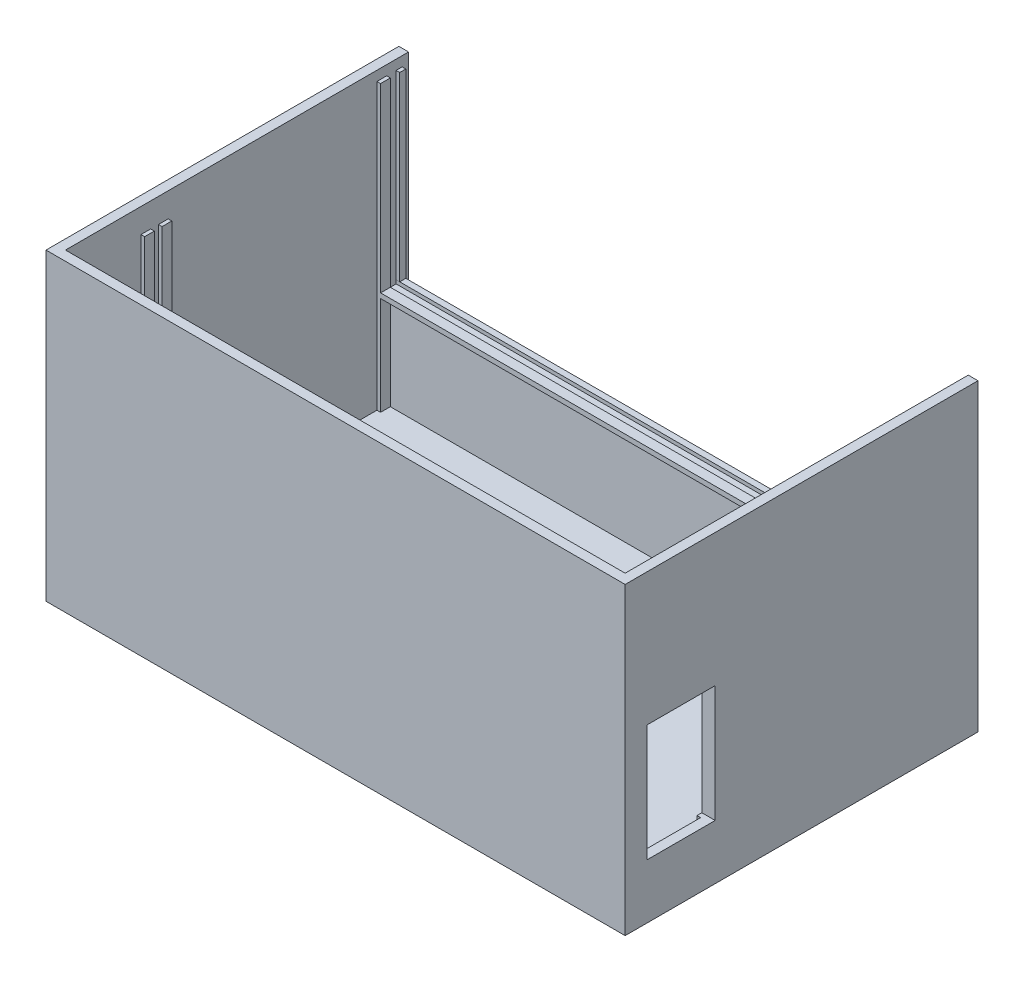
SolidWorks part; units mm, degrees
ref_plane "前视基准面" through (0, 0, 0) normal (0, 0, 1) x (1, 0, 0)
ref_plane "上视基准面" through (0, 0, 0) normal (0, 1, 0) x (1, 0, 0)
ref_plane "右视基准面" through (0, 0, 0) normal (1, 0, 0) x (0, 0, -1)
sketch "草图1" plane through (0, 0, 0) normal (0, 1, 0) x (1, 0, 0)
  line L1 (-86.1247, 66.7751) -> (151.8753, 66.7751)
  line L2 (-86.1247, 66.7751) -> (-86.1247, -73.2249)
  line L3 (-86.1247, -73.2249) -> (151.8753, -73.2249)
  line L4 (151.8753, 66.7751) -> (151.8753, -73.2249)
  dimension "D1" = 140
  dimension "D2" = 238
extrude "凸台-拉伸3" add sketch "草图1" along normal blind 125
shell "抽壳1" thickness 4
sketch "草图2" plane through (0, 0, -62.7751) normal (0, 0, 1) x (1, 0, 0)
  line L1 (-82.1247, 125) -> (-82.1247, 4) construction
  line L2 (147.8753, 125) -> (-82.1247, 125)
  line L3 (147.8753, 125) -> (147.8753, 45)
  line L4 (147.8753, 45) -> (-82.1247, 45)
  line L5 (-82.1247, 125) -> (-82.1247, 45)
  dimension "D1" = 80
extrude "切除-拉伸1" cut sketch "草图2" against normal blind 120
sketch "草图5" plane through (147.8753, 0, 0) normal (-1, 0, 0) x (0, 0, 1)
  line L0 (69.2249, 125) -> (-66.7751, 125) construction
  line L1 (-62.7751, 4) -> (-58.7751, 4)
  line L2 (-62.7751, 4) -> (-62.7751, 121)
  line L3 (-62.7751, 121) -> (-58.7751, 121)
  line L4 (-58.7751, 4) -> (-58.7751, 121)
  dimension "D1" = 4
  dimension "D2" = 4
extrude "凸台-拉伸6" add sketch "草图5" along normal blind 1.5
sketch "草图6" plane through (-82.1247, 0, 0) normal (1, 0, 0) x (0, 0, -1)
  line L0 (66.7751, 125) -> (-69.2249, 125) construction
  line L1 (62.7751, 4) -> (58.7751, 4)
  line L2 (62.7751, 4) -> (62.7751, 121)
  line L3 (62.7751, 121) -> (58.7751, 121)
  line L4 (58.7751, 4) -> (58.7751, 121)
  dimension "D1" = 4
  dimension "D2" = 4
extrude "凸台-拉伸7" add sketch "草图6" along normal blind 1.5
sketch "草图7" plane through (0, 0, -66.7751) normal (0, 0, -1) x (-1, 0, 0)
  line L0 (-151.8753, 125) -> (-147.8753, 125)
  line L1 (-147.8753, 125) -> (-147.8753, 4)
  line L2 (-147.8753, 4) -> (82.1247, 4)
  line L3 (82.1247, 4) -> (82.1247, 125)
  line L4 (82.1247, 125) -> (86.1247, 125)
  line L5 (86.1247, 125) -> (86.1247, 0)
  line L6 (86.1247, 0) -> (-151.8753, 0)
  line L7 (-151.8753, 0) -> (-151.8753, 125)
  line L8 (82.1247, 125) -> (82.1247, 45) construction
  dimension "D1" = 4
extrude "凸台-拉伸8" add sketch "草图7" along normal blind 5
sketch "草图8" plane through (147.8753, 0, 0) normal (-1, 0, 0) x (0, 0, 1)
  line L5 (-66.6457, 46.5) -> (-66.7751, 37.3879)
  line L6 (-66.7751, 4) -> (-66.7751, 45) construction
  line L7 (-66.7751, 37.3879) -> (-69.1457, 45)
  line L8 (-69.1457, 45) -> (-69.1457, 46.5)
  line L9 (-69.1457, 46.5) -> (-66.6457, 46.5)
  line L10 (-66.7751, 45) -> (-62.7751, 45) construction
  dimension "D1" = 1.5
  dimension "D2" = 2.5
  dimension "D3" = 1.5
extrude "凸台-拉伸9" add sketch "草图8" along normal blind 230
sketch "草图9" plane through (146.3753, 0, 0) normal (-1, 0, 0) x (0, 0, 1)
  line L0 (-62.7751, 46.5) -> (-58.7751, 46.5)
  line L1 (-62.7751, 121) -> (-62.7751, 45) construction
  line L2 (-58.7751, 4) -> (-58.7751, 121) construction
  line L3 (-58.7751, 46.5) -> (-58.7751, 44.5)
  line L4 (-58.7751, 44.5) -> (-62.7751, 43)
  line L5 (-62.7751, 45) -> (-62.7751, 4) construction
  line L6 (-62.7751, 43) -> (-62.7751, 46.5)
  line L7 (-66.667, 45) -> (-62.7751, 45) construction
  dimension "D1" = 1.5
  dimension "D2" = 2
  dimension "D3" = 2
extrude "凸台-拉伸10" add sketch "草图9" along normal blind 227
sketch "草图10" plane through (147.8753, 0, 0) normal (-1, 0, 0) x (0, 0, 1)
  line L0 (69.2249, 125) -> (-71.7751, 125) construction
  line L1 (-69.1457, 46.5) -> (-66.6457, 46.5)
  line L2 (-69.1457, 46.5) -> (-69.1457, 121)
  line L3 (-69.1457, 121) -> (-66.6457, 121)
  line L4 (-66.6457, 46.5) -> (-66.6457, 121)
  dimension "D1" = 4
extrude "凸台-拉伸11" add sketch "草图10" along normal blind 1.5
sketch "草图11" plane through (-82.1247, 0, 0) normal (1, 0, 0) x (0, 0, -1)
  line L0 (71.7751, 125) -> (-69.2249, 125) construction
  line L1 (69.1457, 46.5) -> (66.6457, 46.5)
  line L2 (69.1457, 46.5) -> (69.1457, 121)
  line L3 (69.1457, 121) -> (66.6457, 121)
  line L4 (66.6457, 46.5) -> (66.6457, 121)
  dimension "D1" = 4
extrude "凸台-拉伸12" add sketch "草图11" along normal blind 1.5
sketch "草图12" plane through (147.8753, 0, 0) normal (-1, 0, 0) x (0, 0, 1)
  line L0 (69.2249, 4) -> (-58.7751, 4) construction
  line L1 (38.2249, 4) -> (34.2249, 4)
  line L2 (38.2249, 4) -> (38.2249, 115)
  line L3 (38.2249, 115) -> (34.2249, 115)
  line L4 (34.2249, 4) -> (34.2249, 115)
  line L5 (-58.7751, 4) -> (-58.7751, 121) construction
  line L6 (69.2249, 125) -> (-71.7751, 125) construction
  line L8 (27.0249, 4) -> (31.0249, 4)
  line L9 (27.0249, 4) -> (27.0249, 115)
  line L10 (27.0249, 115) -> (31.0249, 115)
  line L11 (31.0249, 4) -> (31.0249, 115)
  dimension "D1" = 93
  dimension "D2" = 4
  dimension "D3" = 10
  dimension "D4" = 10
  dimension "D5" = 3.2
  dimension "D6" = 4
extrude "凸台-拉伸14" add sketch "草图12" along normal blind 1.5
sketch "草图13" plane through (147.8753, 0, 0) normal (-1, 0, 0) x (0, 0, 1)
  line L0 (69.2249, 4) -> (38.2249, 4) construction
  line L1 (69.2249, 4) -> (67.2249, 4)
  line L2 (69.2249, 4) -> (69.2249, 115)
  line L3 (69.2249, 115) -> (67.2249, 115)
  line L4 (67.2249, 4) -> (67.2249, 115)
  line L6 (69.2249, 125) -> (-71.7751, 125) construction
  line L7 (64.2249, 4) -> (60.2249, 4)
  line L8 (64.2249, 4) -> (64.2249, 115)
  line L9 (64.2249, 115) -> (60.2249, 115)
  line L10 (60.2249, 4) -> (60.2249, 115)
  line L11 (69.2249, 125) -> (69.2249, 4) construction
  dimension "D1" = 2
  dimension "D3" = 4
  dimension "D4" = 3
  dimension "D5" = 10
  dimension "D6" = 10
extrude "凸台-拉伸17" add sketch "草图13" along normal blind 1.5
sketch "草图14" plane through (146.3753, 0, 0) normal (-1, 0, 0) x (0, 0, 1)
  line L0 (64.2249, 4) -> (64.2249, 115) construction
  line L1 (36.2249, 79) -> (64.2249, 79) construction
  line L2 (36.2249, 79) -> (36.2249, 14) construction
  line L3 (36.2249, 14) -> (64.2249, 14) construction
  line L4 (64.2249, 79) -> (64.2249, 14) construction
  line L5 (60.2249, 4) -> (38.2249, 4) construction
  line L7 (36.2249, 22.5) -> (64.2249, 22.5)
  line L8 (36.2249, 22.5) -> (36.2249, 70.5)
  line L9 (36.2249, 70.5) -> (64.2249, 70.5)
  line L10 (64.2249, 22.5) -> (64.2249, 70.5)
  point P12 (36.2249, 46.5)
  point P13 (36.2249, 46.5)
  dimension "D1" = 65
  dimension "D2" = 28
  dimension "D3" = 10
  dimension "D4" = 48
extrude "切除-拉伸3" cut sketch "草图14" against normal blind 18
sketch "草图15" plane through (0, 0, -66.7751) normal (0, 0, -1) x (-1, 0, 0)
  line L1 (-147.8753, 4) -> (-147.8753, 37.3879) construction
  line L2 (-132.8753, 31.694) -> (-102.8753, 31.694)
  line L3 (-132.8753, 31.694) -> (-132.8753, 9.694)
  line L4 (-132.8753, 9.694) -> (-102.8753, 9.694)
  line L5 (-102.8753, 31.694) -> (-102.8753, 9.694)
  line L6 (-87.8753, 31.694) -> (-57.8753, 31.694)
  line L7 (-87.8753, 31.694) -> (-87.8753, 9.694)
  line L8 (-87.8753, 9.694) -> (-57.8753, 9.694)
  line L9 (-57.8753, 31.694) -> (-57.8753, 9.694)
  point P8 (-147.8753, 20.694)
  point P9 (-132.8753, 20.694)
  point P12 (-87.8753, 20.694)
  dimension "D1" = 22
  dimension "D2" = 22
  dimension "D3" = 30
  dimension "D4" = 30
  dimension "D5" = 15
  dimension "D6" = 15
extrude "切除-拉伸4" cut sketch "草图15" against normal blind 18
sketch "草图16" plane through (-82.1247, 0, 0) normal (1, 0, 0) x (0, 0, -1)
  line L0 (71.7751, 125) -> (-69.2249, 125) construction
  line L1 (-69.2249, 4) -> (-67.2249, 4)
  line L2 (-69.2249, 4) -> (-69.2249, 115)
  line L3 (-69.2249, 115) -> (-67.2249, 115)
  line L4 (-67.2249, 4) -> (-67.2249, 115)
  dimension "D1" = 2
  dimension "D2" = 10
extrude "凸台-拉伸18" add sketch "草图16" along normal blind 1.5
sketch "草图17" plane through (-82.1247, 0, 0) normal (1, 0, 0) x (0, 0, -1)
  line L0 (58.7751, 4) -> (-67.2249, 4) construction
  line L1 (-64.2249, 4) -> (-60.2249, 4)
  line L2 (-64.2249, 4) -> (-64.2249, 115)
  line L3 (-64.2249, 115) -> (-60.2249, 115)
  line L4 (-60.2249, 4) -> (-60.2249, 115)
  line L5 (71.7751, 125) -> (-69.2249, 125) construction
  line L6 (-69.2249, 125) -> (-69.2249, 115) construction
  dimension "D1" = 4
  dimension "D2" = 10
  dimension "D3" = 5
extrude "凸台-拉伸19" add sketch "草图17" along normal blind 1.5
sketch "草图19" plane through (-82.1247, 0, 0) normal (1, 0, 0) x (0, 0, -1)
  line L0 (58.7751, 4) -> (-60.2249, 4) construction
  line L1 (-38.2249, 4) -> (-34.2249, 4)
  line L2 (-38.2249, 4) -> (-38.2249, 115)
  line L3 (-38.2249, 115) -> (-34.2249, 115)
  line L4 (-34.2249, 4) -> (-34.2249, 115)
  line L5 (-69.2249, 125) -> (-69.2249, 115) construction
  line L6 (71.7751, 125) -> (-69.2249, 125) construction
  dimension "D1" = 4
  dimension "D2" = 31
  dimension "D3" = 10
extrude "凸台-拉伸20" add sketch "草图19" along normal blind 1.5
sketch "草图20" plane through (-82.1247, 0, 0) normal (1, 0, 0) x (0, 0, -1)
  line L0 (58.7751, 4) -> (-34.2249, 4) construction
  line L1 (-31.0249, 4) -> (-27.0249, 4)
  line L2 (-31.0249, 4) -> (-31.0249, 115)
  line L3 (-31.0249, 115) -> (-27.0249, 115)
  line L4 (-27.0249, 4) -> (-27.0249, 115)
  line L5 (71.7751, 125) -> (-69.2249, 125) construction
  line L6 (-69.2249, 125) -> (-69.2249, 115) construction
  dimension "D1" = 4
  dimension "D2" = 10
  dimension "D3" = 38.2
extrude "凸台-拉伸21" add sketch "草图20" along normal blind 1.5
